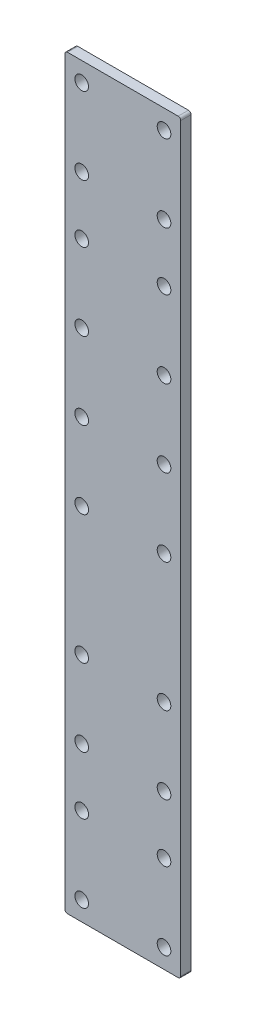
SolidWorks part; units mm, degrees
ref_plane "Front Plane" through (0, 0, 0) normal (0, 0, 1) x (1, 0, 0)
ref_plane "Top Plane" through (0, 0, 0) normal (0, 1, 0) x (1, 0, 0)
ref_plane "Right Plane" through (0, 0, 0) normal (1, 0, 0) x (0, 0, -1)
sketch "Sketch1" plane through (0, 0, 0) normal (0, 0, 1) x (1, 0, 0)
  line L0 (2.2, 0) -> (-2.2, 0) construction
  line L3 (-22.5, -140) -> (22.5, -140)
  line L7 (22.5, 150) -> (-22.5, 150)
  line L9 (0, -2.2) -> (0, 2.2) construction
  line L10 (-22.5, 150) -> (-22.5, -140)
  line L11 (22.5, 150) -> (22.5, -140)
  dimension "D1" = 45
  dimension "D2" = 150
  dimension "D5" = 45
  dimension "D6" = 22.5
  dimension "D7" = 290
  dimension "D8" = 22.5
extrude "Boss-Extrude1" add sketch "Sketch1" along normal blind 4
hole_wizard "M5 Clearance Hole1" positions "Sketch3" profile "Sketch2" hole size "M5" standard "ISO" end condition through all
sketch "Sketch3" plane through (0, 0, 4) normal (0, 0, 1) x (1, 0, 0)
  line L0 (0, 49.8121) -> (0, -39.3133) construction
  line L3 (0, -2.2) -> (0, 2.2) construction
  line L4 (-16, -132.5) -> (-16, 111.9546)
  line L6 (22.5, 150) -> (-22.5, 150) construction
  line L8 (2.2, 0) -> (-2.2, 0) construction
  point P0 (-16, 142.5)
  point P2 (-16, 112.5)
  point P4 (-16, -102.5)
  point P6 (-16, -132.5)
  point P28 (16, -132.5)
  point P29 (16, -102.5)
  point P30 (16, 112.5)
  point P31 (16, 142.5)
  point P32 (-16, 30)
  point P34 (-16, 0)
  point P40 (16, 0)
  point P41 (16, 30)
  point P43 (-16, 90)
  point P45 (-16, 60)
  point P47 (-16, -50)
  point P49 (-16, -80)
  point P52 (16, -80)
  point P53 (16, -50)
  point P54 (16, 60)
  point P55 (16, 90)
  dimension "D1" = 16
  dimension "D2" = 30
  dimension "D3" = 7.5
  dimension "D4" = 30
  dimension "D6" = 16
  dimension "D7" = 16
  dimension "D8" = 16
  dimension "D9" = 30
  dimension "D10" = 30
  dimension "D11" = 50
  dimension "D12" = 30
  dimension "D13" = 30
  dimension "D14" = 30
  dimension "D15" = 22.5
sketch "Sketch2" plane through (-16, 142.5, 4) normal (1, 0, 0) x (0, -1, 0)
  line L0 (0, 0) -> (0, 4)
  line L1 (0, 4) -> (2.65, 4)
  line L2 (2.65, 4) -> (2.65, 0)
  line L5 (2.65, 0) -> (0, 0)
  line L11 (0, -6.35) -> (0, 107.95) construction
  dimension "Thru Hole Dia." = 5.3
  dimension "Thru Hole Depth" = 4
fillet "Fillet1" radius 1 4 edges at (-22.5, -140, 2) (22.5, -140, 2) (22.5, 150, 2) (-22.5, 150, 2)
